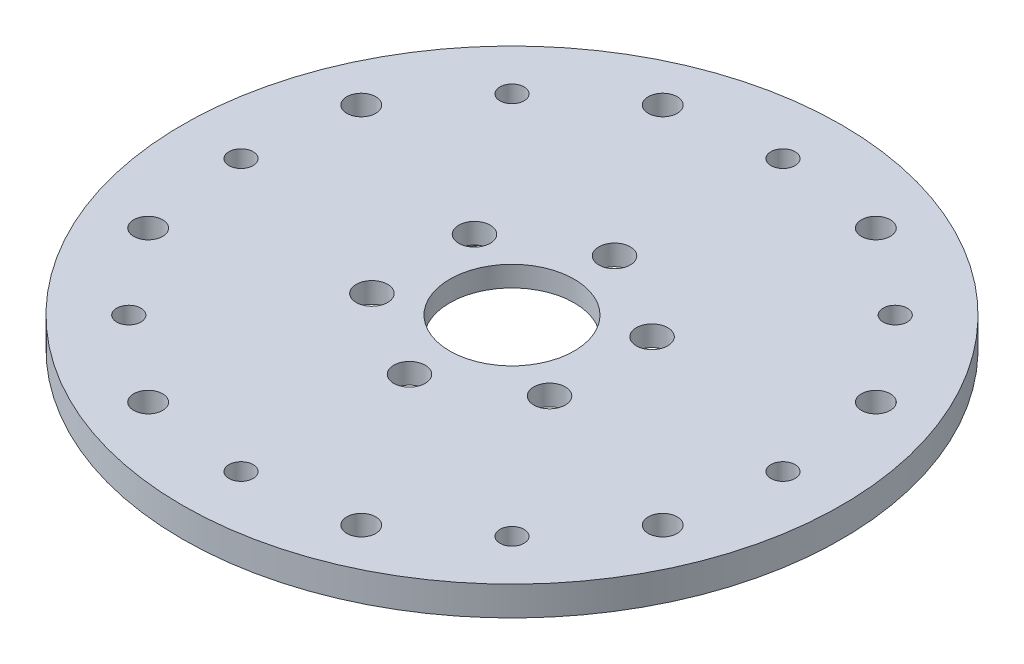
SolidWorks part; units mm, degrees
material "S-玻璃纤维"
ref_plane "前视基准面" through (0, 0, 0) normal (0, 0, 1) x (1, 0, 0)
ref_plane "上视基准面" through (0, 0, 0) normal (0, 1, 0) x (1, 0, 0)
ref_plane "右视基准面" through (0, 0, 0) normal (1, 0, 0) x (0, 0, -1)
other "Configuration Table"
sketch "草图1" plane through (0, 0, 0) normal (0, 1, 0) x (1, 0, 0)
  circle A0 centre (0, 0) radius 45
  dimension "D1" = 90
extrude "凸台-拉伸1" add sketch "草图1" along normal blind 4
sketch "草图2" plane through (0, 4, 0) normal (0, 1, 0) x (1, 0, 0)
  circle A0 centre (0, 14) radius 2.15
  dimension "D1" = 4.3
  dimension "D2" = 14
extrude "切除-拉伸1" cut sketch "草图2" against normal through all both
pattern_circular "阵列(圆周)1" count 6 over 360 about axis through (0, 0, 0) along (0, 1, 0) of "切除-拉伸1"
sketch "草图3" plane through (0, 4, 0) normal (0, 1, 0) x (1, 0, 0)
  circle A0 centre (0, 0) radius 8.5
  dimension "D1" = 17
extrude "切除-拉伸2" cut sketch "草图3" against normal through all both
sketch "草图4" plane through (0, 4, 0) normal (0, 1, 0) x (1, 0, 0)
  circle A0 centre (0, 37) radius 1.65
  dimension "D1" = 3.3
  dimension "D2" = 37
extrude "切除-拉伸3" cut sketch "草图4" against normal through all both
pattern_circular "阵列(圆周)2" count 8 over 360 about axis through (0, 0, 0) along (0, 1, 0) of "切除-拉伸3"
sketch "草图5" plane through (0, 0, 0) normal (0, -1, 0) x (1, 0, 0)
  circle A0 centre (0, 0) radius 17.6
  dimension "D1" = 35.2
extrude "切除-拉伸4" cut sketch "草图5" against normal blind 1.2
sketch "草图6" plane through (0, 4, 0) normal (0, 1, 0) x (1, 0, 0)
  line L0 (0, -0.5196) -> (0, -50000.5196) construction
  line L1 (0, 0) -> (19134.1716, -46193.9766) construction
  circle A0 centre (0, 0) radius 40 construction
  circle A1 centre (14.5515, -35.1305) radius 1.975
  dimension "D1" = 80
  dimension "D2" = 3.95
  dimension "D3" = 22.5
extrude "切除-拉伸5" cut sketch "草图6" against normal through all both
pattern_circular "阵列(圆周)3" count 8 over 360 about axis through (0, 0, 0) along (0, 1, 0) of "切除-拉伸5"
